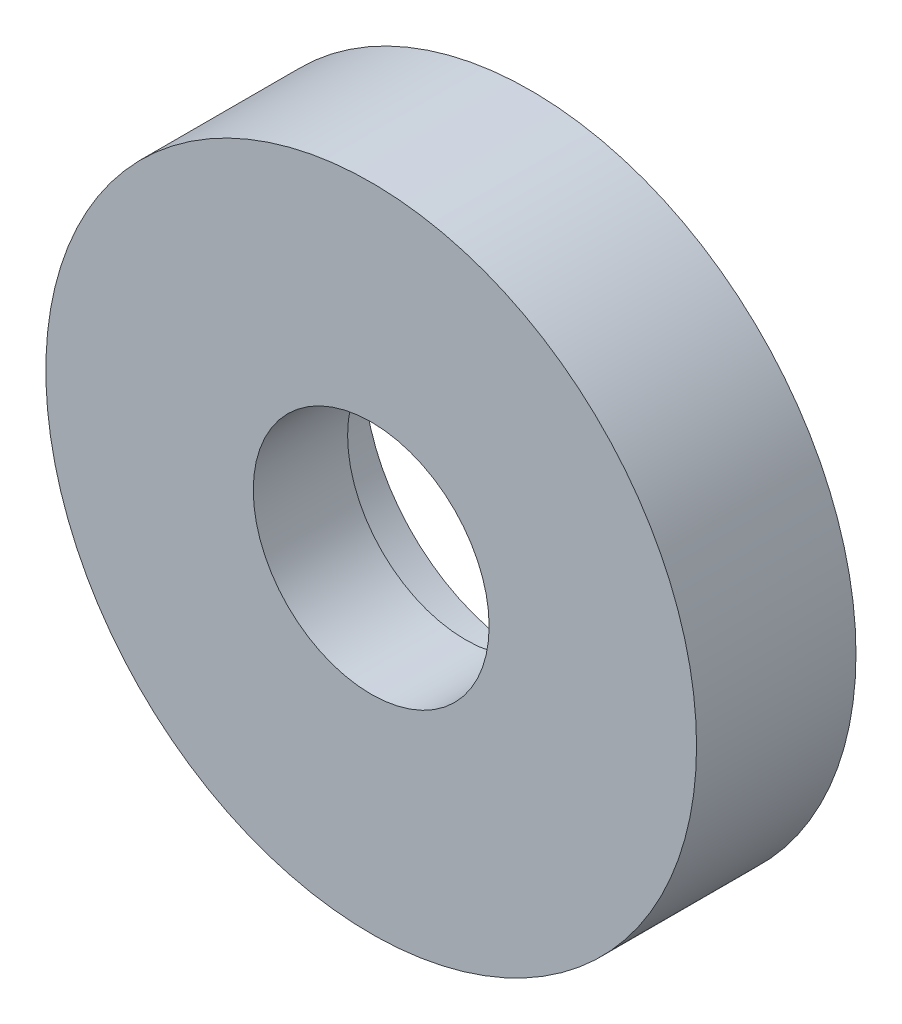
SolidWorks part; units mm, degrees
ref_plane "Ebene vorne" through (0, 0, 0) normal (0, 0, 1) x (1, 0, 0)
ref_plane "Ebene oben" through (0, 0, 0) normal (0, 1, 0) x (1, 0, 0)
ref_plane "Ebene rechts" through (0, 0, 0) normal (1, 0, 0) x (0, 0, -1)
sketch "Skizze1" plane through (0, 0, 0) normal (0, 0, 1) x (1, 0, 0)
  circle A0 centre (0, 0) radius 7.25
  circle A1 centre (0, 0) radius 20
  dimension "D1" = 40
  dimension "D2" = 14.5
extrude "Aufsatz-Linear austragen1" add sketch "Skizze1" along normal blind 9.8
sketch "Skizze2" plane through (0, 0, 0) normal (0, 0, -1) x (-1, 0, 0)
  circle A0 centre (0, 0) radius 10.25
  dimension "D1" = 20.5
extrude "Schnitt-Linear austragen1" cut sketch "Skizze2" against normal blind 4
